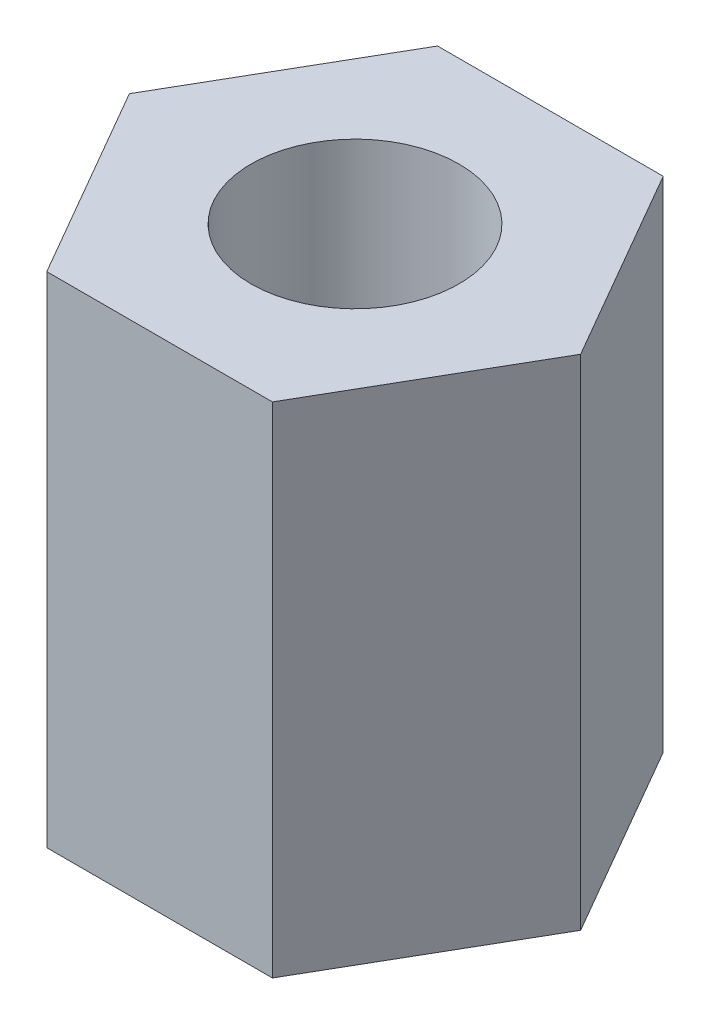
SolidWorks part; units mm, degrees
material "Nylon 101"
ref_plane "Front Plane" through (0, 0, 0) normal (0, 0, 1) x (1, 0, 0)
ref_plane "Top Plane" through (0, 0, 0) normal (0, 1, 0) x (1, 0, 0)
ref_plane "Right Plane" through (0, 0, 0) normal (1, 0, 0) x (0, 0, -1)
sketch "Sketch1" plane through (0, 0, 0) normal (0, 1, 0) x (1, 0, 0)
  line L1 (2.7135, 0) -> (1.3568, 2.35)
  line L2 (1.3568, 2.35) -> (-1.3568, 2.35)
  line L3 (-1.3568, 2.35) -> (-2.7135, 0)
  line L4 (-2.7135, 0) -> (-1.3568, -2.35)
  line L5 (-1.3568, -2.35) -> (1.3568, -2.35)
  line L6 (1.3568, -2.35) -> (2.7135, 0)
  circle A0 centre (0, 0) radius 2.35 construction
  circle A1 centre (0, 0) radius 1.25
  dimension "D2" = 2.5
  dimension "D1" = 4.7
extrude "Boss-Extrude1" add sketch "Sketch1" along normal blind 6
